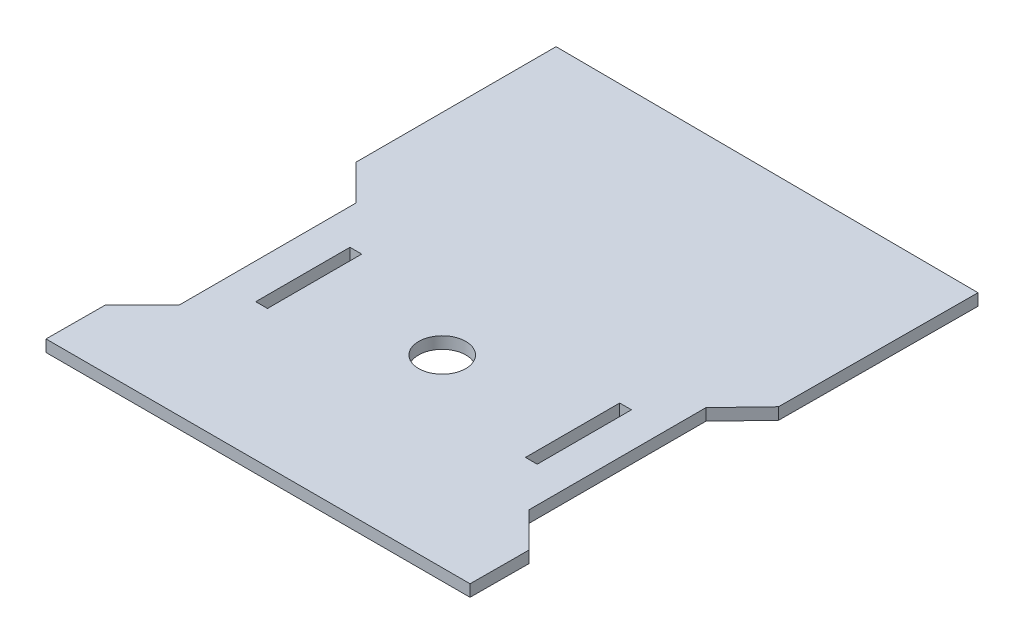
SolidWorks part; units mm, degrees
ref_plane "Front Plane" through (0, 0, 0) normal (0, 0, 1) x (1, 0, 0)
ref_plane "Top Plane" through (0, 0, 0) normal (0, 1, 0) x (1, 0, 0)
ref_plane "Right Plane" through (0, 0, 0) normal (1, 0, 0) x (0, 0, -1)
sketch "Sketch2" plane through (0, 0, 0) normal (0, 1, 0) x (1, 0, 0)
  line L0 (-124.7602, 128.8096) -> (55.2398, 127.9134)
  line L1 (55.2398, 127.9134) -> (54.7419, 27.9134)
  line L2 (54.7419, 27.9134) -> (39.7419, 27.9134)
  line L3 (39.7419, 27.9134) -> (39.7419, -47.0866)
  line L4 (39.7419, -47.0866) -> (54.5427, -61.8875)
  line L5 (54.5427, -61.8875) -> (54.4183, -86.8875)
  line L6 (54.4183, -86.8875) -> (-125.5817, -86.8875)
  line L7 (-125.5817, -86.8875) -> (-125.4573, -61.8875)
  line L8 (-125.4573, -61.8875) -> (-109.7602, -46.1904)
  line L9 (-109.7602, -46.1904) -> (-109.7602, 28.8096)
  line L10 (-109.7602, 28.8096) -> (-124.7602, 28.8096)
  line L11 (-124.7602, 28.8096) -> (-124.7602, 128.8096)
  point P2 (-117.2602, 28.8096)
  dimension "D1" = 180
  dimension "D2" = 100
  dimension "D3" = 15
  dimension "D4" = 15
  dimension "D5" = 180
  dimension "D6" = 75
  dimension "D7" = 135
  dimension "D8" = 135
  dimension "D9" = 25
  dimension "D10" = 25
  dimension "D11" = 100
  dimension "D12" = 115.697
extrude "Boss-Extrude1" add sketch "Sketch2" along normal blind 5
sketch "Sketch4" plane through (0, 5, 0) normal (0, 1, 0) x (1, 0, 0)
  line L0 (-109.7602, 28.8096) -> (-124.7602, 43.8096)
  line L1 (-124.7602, 128.8096) -> (-124.7602, 28.8096) construction
  line L2 (-124.7602, 28.8096) -> (-109.7602, 28.8096) construction
  line L3 (-124.7602, 43.8096) -> (-124.7602, 28.8096)
  line L4 (-124.7602, 28.8096) -> (-109.7602, 28.8096)
  line L5 (39.7419, 27.9134) -> (54.8203, 43.668)
  line L6 (54.7419, 27.9134) -> (55.2398, 127.9134) construction
  line L7 (54.8203, 43.668) -> (54.7419, 27.9134)
  line L8 (54.7419, 27.9134) -> (39.7419, 27.9134)
  dimension "D1" = 45
extrude "Cut-Extrude2" cut sketch "Sketch4" against normal blind 5
sketch "Sketch5" plane through (0, 5, 0) normal (0, 1, 0) x (1, 0, 0)
  line L0 (-109.7602, 28.8096) -> (-109.7602, -46.1904) construction
  line L1 (-89.7602, 11.3096) -> (-94.7602, 11.3096)
  line L2 (-89.7602, 11.3096) -> (-89.7602, -28.6904)
  line L3 (-89.7602, -28.6904) -> (-94.7602, -28.6904)
  line L4 (-94.7602, 11.3096) -> (-94.7602, -28.6904)
  line L5 (-89.7602, 11.3096) -> (-94.7602, -28.6904) construction
  line L6 (-89.7602, -28.6904) -> (-94.7602, 11.3096) construction
  line L7 (19.7419, -28.6904) -> (24.7419, -28.6904)
  line L8 (19.7419, -28.6904) -> (19.7419, 11.3096)
  line L9 (19.7419, 11.3096) -> (24.7419, 11.3096)
  line L10 (24.7419, -28.6904) -> (24.7419, 11.3096)
  line L11 (19.7419, -28.6904) -> (24.7419, 11.3096) construction
  line L12 (19.7419, 11.3096) -> (24.7419, -28.6904) construction
  line L13 (39.7419, -47.0866) -> (39.7419, 27.9134) construction
  point P0 (-92.2602, -8.6904)
  point P5 (22.2419, -8.6904)
  point P15 (39.7419, -9.5866)
  dimension "D1" = 5
  dimension "D2" = 40
  dimension "D3" = 15
  dimension "D4" = 17.5
  dimension "D5" = 40
  dimension "D6" = 5
  dimension "D7" = 15
extrude "Cut-Extrude3" cut sketch "Sketch5" against normal blind 10
sketch "Sketch6" plane through (0, 5, 0) normal (0, 1, 0) x (1, 0, 0)
  circle A0 centre (-35.5817, -8.6904) radius 10
  dimension "D1" = 20
extrude "Cut-Extrude4" cut sketch "Sketch6" against normal blind 10
